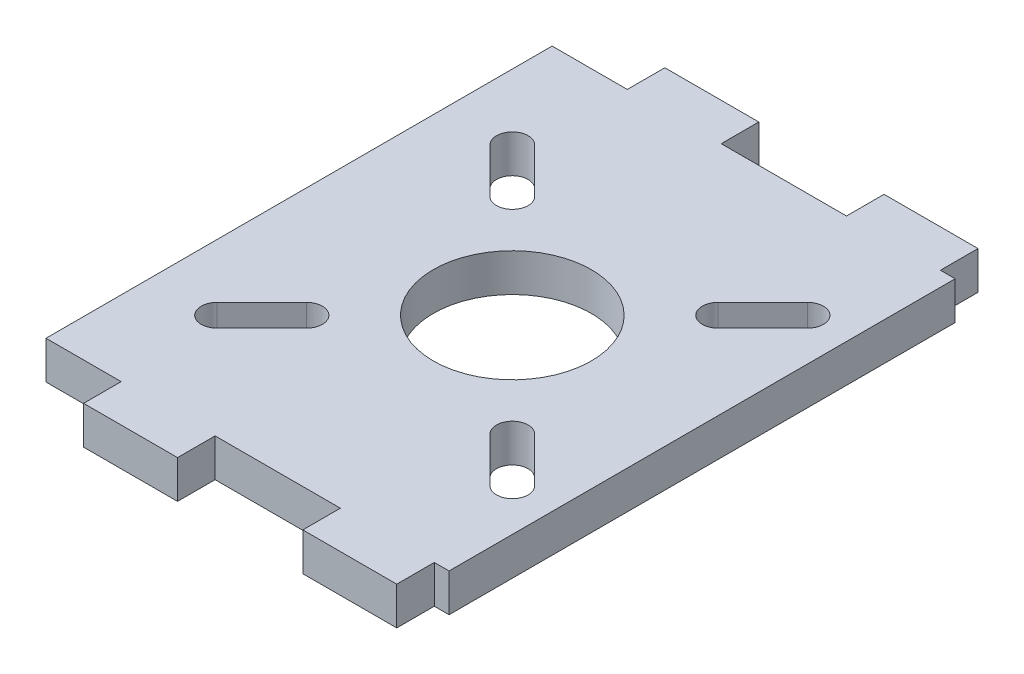
SolidWorks part; units mm, degrees
ref_plane "Front Plane" through (0, 0, 0) normal (0, 0, 1) x (1, 0, 0)
ref_plane "Top Plane" through (0, 0, 0) normal (0, 1, 0) x (1, 0, 0)
ref_plane "Right Plane" through (0, 0, 0) normal (1, 0, 0) x (0, 0, -1)
sketch "Sketch1" plane through (0, 0, 0) normal (0, 1, 0) x (1, 0, 0)
  line L0 (-33.7103, 36.1075) -> (-33.7103, -43.8925)
  line L9 (30.0005, -43.8925) -> (30.0005, 36.1075)
  line L10 (30.0005, 36.1075) -> (27.6705, 36.1075)
  line L11 (27.6705, 36.1075) -> (27.6705, 42.0476)
  line L12 (27.6705, 42.0476) -> (12.8203, 42.0476)
  line L13 (12.8203, 42.0476) -> (12.8203, 36.1075)
  line L14 (12.8203, 36.1075) -> (-6.98, 36.1075)
  line L15 (-6.98, 36.1075) -> (-6.98, 42.0476)
  line L16 (-6.98, 42.0476) -> (-21.8302, 42.0476)
  line L17 (-21.8302, 42.0476) -> (-21.8302, 36.1075)
  line L18 (-21.8302, 36.1075) -> (-33.7103, 36.1075)
  line L21 (-23.3358, -27.2283) -> (-16.2647, -20.1572) construction
  line L22 (-25.1036, -25.4605) -> (-18.0325, -18.3895)
  line L23 (-21.568, -28.9961) -> (-14.497, -21.925)
  line L25 (-21.8302, -43.8925) -> (-33.7103, -43.8925)
  line L26 (-23.3358, 19.4433) -> (-16.2647, 12.3722) construction
  line L27 (-21.568, 21.2111) -> (-14.497, 14.14)
  line L28 (-25.1036, 17.6756) -> (-18.0325, 10.6045)
  line L29 (23.3358, 19.4433) -> (16.2647, 12.3722) construction
  line L30 (25.1036, 17.6756) -> (18.0325, 10.6045)
  line L31 (21.568, 21.2111) -> (14.497, 14.14)
  line L32 (23.3358, -27.2283) -> (16.2647, -20.1572) construction
  line L33 (21.568, -28.9961) -> (14.497, -21.925)
  line L34 (25.1036, -25.4605) -> (18.0325, -18.3895)
  line L36 (-21.8302, -49.8326) -> (-21.8302, -43.8925)
  line L37 (-6.98, -49.8326) -> (-21.8302, -49.8326)
  line L38 (-6.98, -43.8925) -> (-6.98, -49.8326)
  line L39 (12.8203, -43.8925) -> (-6.98, -43.8925)
  line L40 (12.8203, -49.8326) -> (12.8203, -43.8925)
  line L41 (27.6705, -49.8326) -> (12.8203, -49.8326)
  line L42 (27.6705, -43.8925) -> (27.6705, -49.8326)
  line L43 (30.0005, -43.8925) -> (27.6705, -43.8925)
  circle A0 centre (0, -3.8925) radius 12.5
  arc A5 (-25.1036, -25.4605) -> (-21.568, -28.9961) centre (-23.3358, -27.2283) ccw
  arc A6 (-14.497, -21.925) -> (-18.0325, -18.3895) centre (-16.2647, -20.1572) ccw
  arc A7 (-21.568, 21.2111) -> (-25.1036, 17.6756) centre (-23.3358, 19.4433) ccw
  arc A8 (-18.0325, 10.6045) -> (-14.497, 14.14) centre (-16.2647, 12.3722) ccw
  arc A9 (25.1036, 17.6756) -> (21.568, 21.2111) centre (23.3358, 19.4433) ccw
  arc A10 (14.497, 14.14) -> (18.0325, 10.6045) centre (16.2647, 12.3722) ccw
  arc A11 (21.568, -28.9961) -> (25.1036, -25.4605) centre (23.3358, -27.2283) ccw
  arc A12 (18.0325, -18.3895) -> (14.497, -21.925) centre (16.2647, -20.1572) ccw
  point P34 (-19.8003, -23.6928)
  point P44 (-19.8003, 15.9078)
  point P51 (19.8003, 15.9078)
  point P58 (19.8003, -23.6928)
  point P63 (0, -3.8925)
  dimension "D1" = 10
  dimension "2.5" = 2.5
  dimension "D3" = 25
  dimension "D4" = 80
  dimension "D5" = 80
extrude "Boss-Extrude1" add sketch "Sketch1" along normal blind 6
